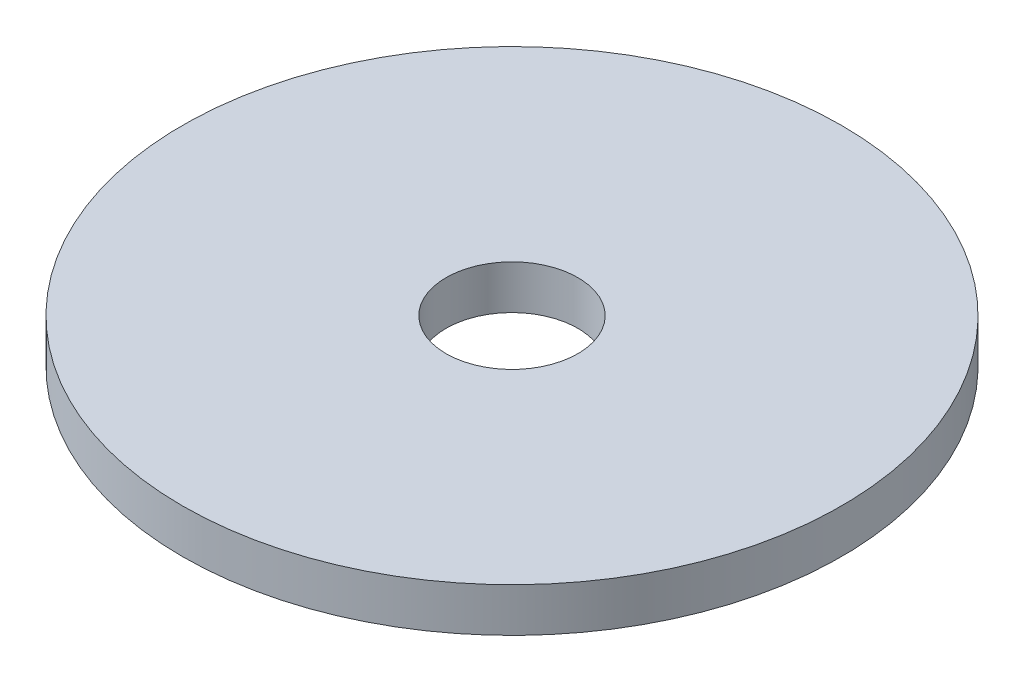
SolidWorks part; units mm, degrees
material "不锈钢 (铁素体)"
ref_plane "前视基准面" through (0, 0, 0) normal (0, 0, 1) x (1, 0, 0)
ref_plane "上视基准面" through (0, 0, 0) normal (0, 1, 0) x (1, 0, 0)
ref_plane "右视基准面" through (0, 0, 0) normal (1, 0, 0) x (0, 0, -1)
sketch "草图1" plane through (0, 0, 0) normal (0, 1, 0) x (1, 0, 0)
  circle A0 centre (0, 0) radius 15
  circle A1 centre (0, 0) radius 3
  dimension "D1" = 30
  dimension "D2" = 6
extrude "凸台-拉伸1" add sketch "草图1" along normal blind 2
